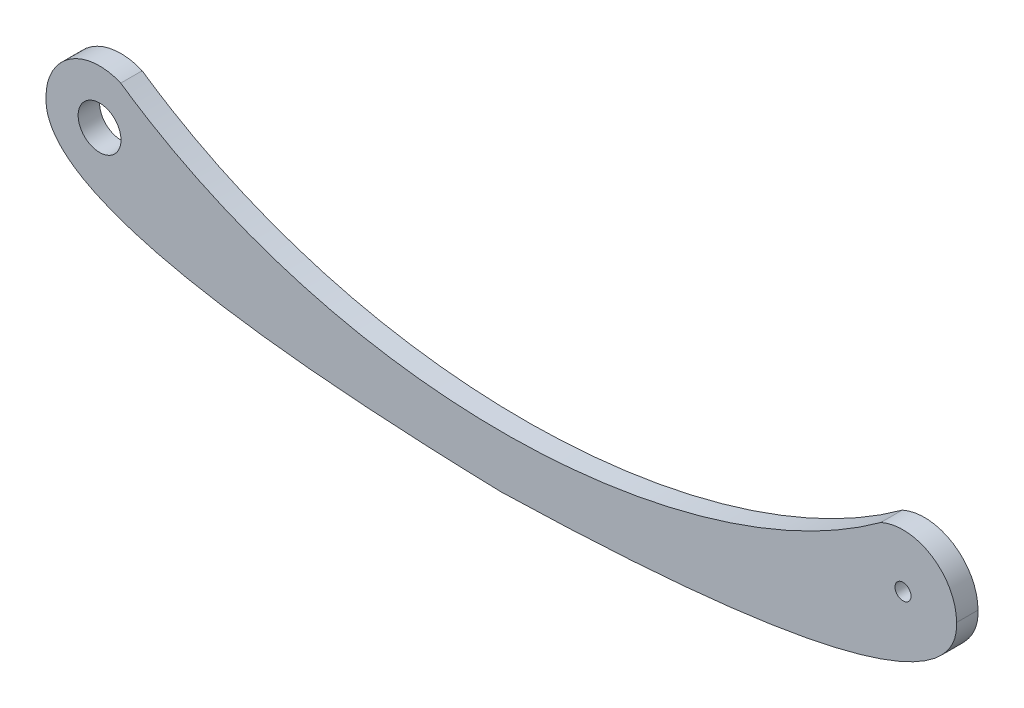
SolidWorks part; units mm, degrees
ref_plane "前视基准面" through (0, 0, 0) normal (0, 0, 1) x (1, 0, 0)
ref_plane "上视基准面" through (0, 0, 0) normal (0, 1, 0) x (1, 0, 0)
ref_plane "右视基准面" through (0, 0, 0) normal (1, 0, 0) x (0, 0, -1)
sketch "草图1" plane through (0, 0, 0) normal (0, 0, 1) x (1, 0, 0)
  line L0 (0, 0) -> (150, 0) construction
  line L4 (75, 0) -> (75, -30.7931) construction
  circle A0 centre (0, 0) radius 4
  circle A1 centre (150, 0) radius 1.5
  arc A2 (3.948, 9.1877) -> (-10, 0) centre (0, 0) ccw
  arc A3 (160, 0) -> (145.866, 9.1055) centre (150, 0) ccw
  spline S0 degree 3 poles (3.948, 9.1877) (46.9065, -20.3737) (110.5517, -16.707) (145.866, 9.1055) knots 0.022449 0.022449 0.022449 0.022449 0.850781 0.850781 0.850781 0.850781
  spline S1 degree 2 poles (-10, 0) (-10.8902, -19.1353) (75, -21.402) knots 0 0 0 1 1 1
  spline S2 degree 2 poles (160, 0) (160.8902, -19.1353) (75, -21.402) knots 0 0 0 1 1 1
  dimension "D1" = 150
extrude "凸台-拉伸1" add sketch "草图1" along normal blind 4
